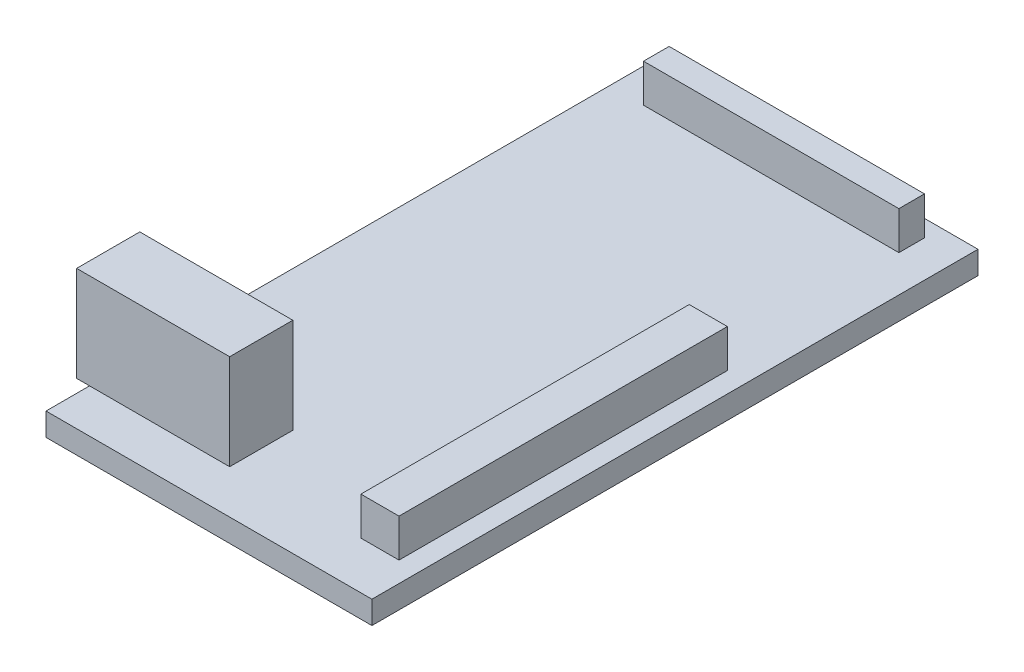
SolidWorks part; units mm, degrees
ref_plane "Front Plane" through (0, 0, 0) normal (0, 0, 1) x (1, 0, 0)
ref_plane "Top Plane" through (0, 0, 0) normal (0, 1, 0) x (1, 0, 0)
ref_plane "Right Plane" through (0, 0, 0) normal (1, 0, 0) x (0, 0, -1)
sketch "Sketch1" plane through (0, 0, 0) normal (0, 1, 0) x (1, 0, 0)
  line L1 (0, 0) -> (17.1, 0)
  line L2 (0, 0) -> (0, -31.8)
  line L3 (0, -31.8) -> (17.1, -31.8)
  line L4 (17.1, 0) -> (17.1, -31.8)
  dimension "D1" = 17.1
  dimension "D2" = 31.8
extrude "Boss-Extrude1" add sketch "Sketch1" along normal blind 1.2
sketch "Sketch2" plane through (0, 1.2, 0) normal (0, 1, 0) x (1, 0, 0)
  line L1 (1.7787, -0.886) -> (15.1784, -0.886)
  line L2 (1.7787, -0.886) -> (1.7787, -2.2288)
  line L3 (1.7787, -2.2288) -> (15.1784, -2.2288)
  line L4 (15.1784, -0.886) -> (15.1784, -2.2288)
  line L5 (14.0356, -12.0858) -> (16.0356, -12.0858)
  line L6 (14.0356, -12.0858) -> (14.0356, -29.314)
  line L7 (14.0356, -29.314) -> (16.0356, -29.314)
  line L8 (16.0356, -12.0858) -> (16.0356, -29.314)
extrude "Boss-Extrude2" add sketch "Sketch2" along normal blind 2
sketch "Sketch3" plane through (0, 1.2, 0) normal (0, 1, 0) x (1, 0, 0)
  line L1 (-0.6784, -26.1998) -> (7.35, -26.1998)
  line L2 (-0.6784, -26.1998) -> (-0.6784, -29.514)
  line L3 (-0.6784, -29.514) -> (7.35, -29.514)
  line L4 (7.35, -26.1998) -> (7.35, -29.514)
extrude "Boss-Extrude3" add sketch "Sketch3" along normal blind 5
